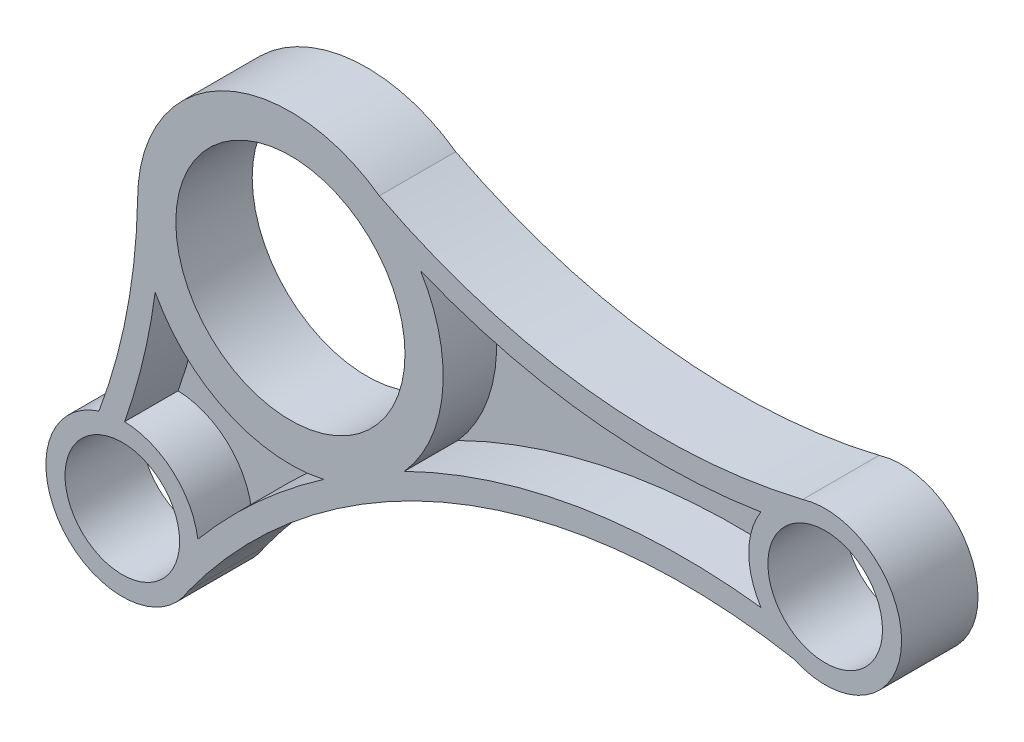
SolidWorks part; units mm, degrees
ref_plane "Front Plane" through (0, 0, 0) normal (0, 0, 1) x (1, 0, 0)
ref_plane "Top Plane" through (0, 0, 0) normal (0, 1, 0) x (1, 0, 0)
ref_plane "Right Plane" through (0, 0, 0) normal (1, 0, 0) x (0, 0, -1)
sketch "Sketch3" plane through (0, 0, 0) normal (0, 0, 1) x (1, 0, 0)
  circle A1 centre (176.9454, 56.9314) radius 10
  circle A3 centre (176.9454, 56.9314) radius 7.5
  circle A6 centre (84.9454, 20.9314) radius 10
  circle A7 centre (84.9454, 20.9314) radius 7.5
  arc A8 (172.7923, 47.8346) -> (93.5995, 15.9208) centre (158.4848, -30.8756) ccw
  arc A9 (174.0026, 66.4886) -> (118.5819, 73.1977) centre (155.3025, 144.2723) cw
  arc A10 (86.9454, 56.9314) -> (81.8842, 30.4513) centre (6.9607, 58.4954) cw
  arc A11 (168.5299, 62.3331) -> (123.9814, 67.4089) centre (155.3025, 144.2723) cw
  arc A12 (111.3077, 37.413) -> (94.8374, 22.3973) centre (158.4848, -30.8756) ccw
  arc A13 (89.2452, 47.6201) -> (85.2485, 30.9268) centre (6.9607, 58.4954) cw
  arc A14 (168.5299, 62.3331) -> (123.9814, 67.4089) centre (155.3025, 144.2723) cw
  arc A15 (174.7039, 63.5717) -> (117.2049, 70.5324) centre (155.3025, 144.2723) cw construction
  arc A16 (174.7039, 63.5717) -> (117.2049, 70.5324) centre (155.3025, 144.2723) cw construction
  arc A17 (168.5406, 51.513) -> (121.8606, 43.6071) centre (158.4848, -30.8756) ccw
  arc A18 (89.9449, 56.8728) -> (84.6938, 29.3997) centre (6.9607, 58.4954) cw construction
  circle A19 centre (106.9454, 56.9314) radius 15
  circle A20 centre (106.9454, 56.9314) radius 20
  point P36 (0, 0)
  dimension "D1" = 20
  dimension "D2" = 15
  dimension "D3" = 70
  dimension "D4" = 30
  dimension "D5" = 40
  dimension "D7" = 22
  dimension "D10" = 15
  dimension "D8" = 36
  dimension "D13" = 3
  dimension "D15" = 3
extrude "Boss-Extrude1" add sketch "Sketch3" along normal blind 10 contours A20 A12 A6 A8 A1 A17 | A20 A10 A6 A13 | A20 A11 A1 A9 | A20 A19 | A6 A7 | A1 A3
sketch "Sketch4" plane through (0, 0, 0) normal (0, 0, 1) x (1, 0, 0)
  arc A0 (94.8374, 22.3973) -> (85.2485, 30.9268) centre (84.9454, 20.9314) ccw construction
  arc A1 (85.2485, 30.9268) -> (89.2452, 47.6201) centre (6.9607, 58.4954) ccw construction
  arc A2 (89.2452, 47.6201) -> (111.3077, 37.413) centre (106.9454, 56.9314) ccw construction
  arc A3 (111.3077, 37.413) -> (94.8374, 22.3973) centre (158.4848, -30.8756) ccw construction
  arc A4 (94.8374, 22.3973) -> (85.2485, 30.9268) centre (84.9454, 20.9314) ccw
  arc A5 (85.2485, 30.9268) -> (89.2452, 47.6201) centre (6.9607, 58.4954) ccw
  arc A6 (89.2452, 47.6201) -> (111.3077, 37.413) centre (106.9454, 56.9314) ccw
  arc A7 (111.3077, 37.413) -> (94.8374, 22.3973) centre (158.4848, -30.8756) ccw
  arc A8 (168.5299, 62.3331) -> (168.5406, 51.513) centre (176.9454, 56.9314) ccw construction
  arc A9 (168.5406, 51.513) -> (121.8606, 43.6071) centre (158.4848, -30.8756) ccw construction
  arc A10 (123.9814, 67.4089) -> (168.5299, 62.3331) centre (155.3025, 144.2723) ccw construction
  arc A11 (121.8606, 43.6071) -> (123.9814, 67.4089) centre (106.9454, 56.9314) ccw construction
  arc A12 (168.5299, 62.3331) -> (168.5406, 51.513) centre (176.9454, 56.9314) ccw
  arc A13 (168.5406, 51.513) -> (121.8606, 43.6071) centre (158.4848, -30.8756) ccw
  arc A14 (123.9814, 67.4089) -> (168.5299, 62.3331) centre (155.3025, 144.2723) ccw
  arc A15 (121.8606, 43.6071) -> (123.9814, 67.4089) centre (106.9454, 56.9314) ccw
extrude "Boss-Extrude3" add sketch "Sketch4" along normal blind 3
